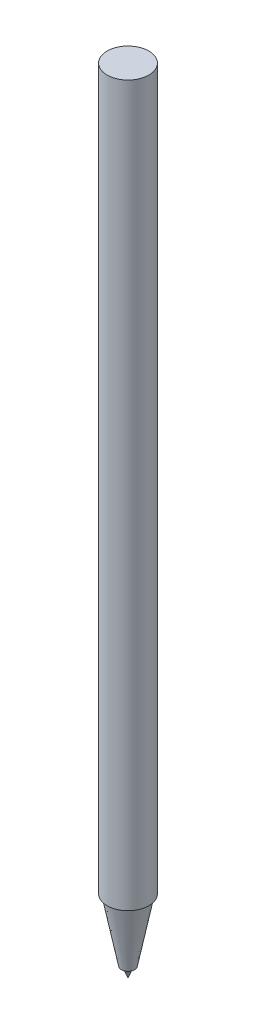
SolidWorks part; units mm, degrees
ref_plane "Front" through (0, 0, 0) normal (0, 0, 1) x (1, 0, 0)
ref_plane "Top" through (0, 0, 0) normal (0, 1, 0) x (1, 0, 0)
ref_plane "Right" through (0, 0, 0) normal (1, 0, 0) x (0, 0, -1)
sketch "Sketch1" plane through (0, 0, 0) normal (0, 1, 0) x (1, 0, 0)
  circle A0 centre (0, 0) radius 4
  dimension "D1" = 8
extrude "Boss-Extrude1" add sketch "Sketch1" along normal blind 138
sketch "Sketch2" plane through (0, 0, 0) normal (0, -1, 0) x (1, 0, 0)
  circle A2 centre (0, 0) radius 3.6
  circle A3 centre (0, 0) radius 3.6
  dimension "D1" = 0.4
extrude "Boss-Extrude2" add sketch "Sketch2" along normal blind 12 draft 11
sketch "Sketch3" plane through (0, -12, 0) normal (0, -1, 0) x (1, 0, 0)
  circle A2 centre (0, 0) radius 0.7674
  circle A3 centre (0, 0) radius 0.7674
  dimension "D1" = 0.5
extrude "Boss-Extrude3" add sketch "Sketch3" along normal blind 5 draft 21
